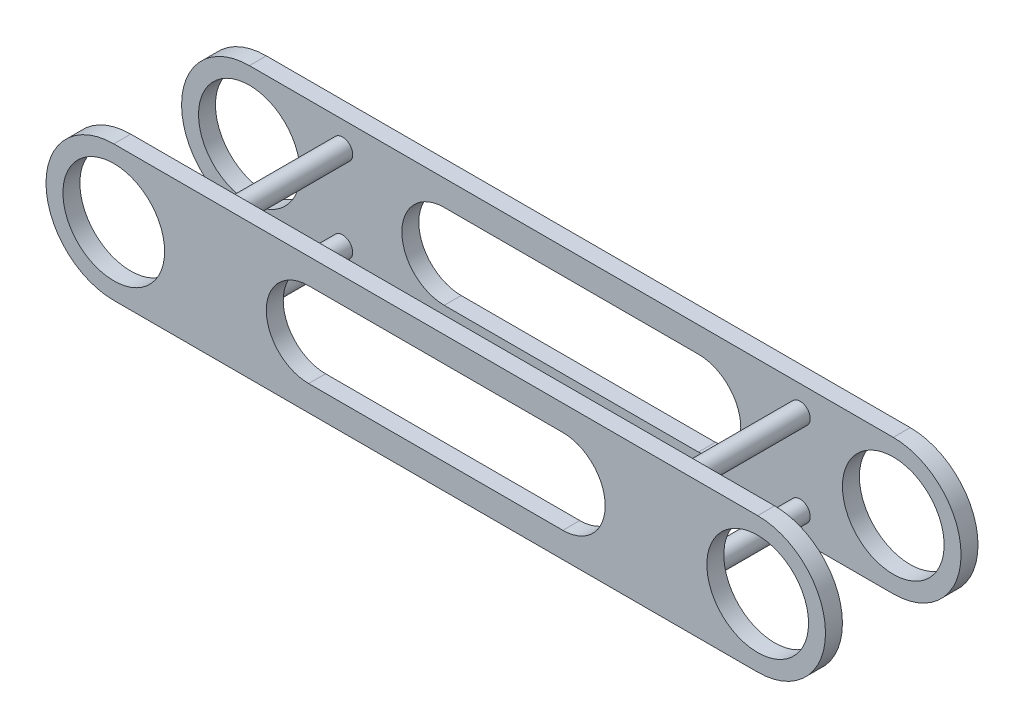
SolidWorks part; units mm, degrees
ref_plane "Front Plane" through (0, 0, 0) normal (0, 0, 1) x (1, 0, 0)
ref_plane "Top Plane" through (0, 0, 0) normal (0, 1, 0) x (1, 0, 0)
ref_plane "Right Plane" through (0, 0, 0) normal (1, 0, 0) x (0, 0, -1)
sketch "Sketch2" plane through (0, 0, 0) normal (0, 0, 1) x (1, 0, 0)
  circle A0 centre (0, 0) radius 30
  dimension "D1" = 60
extrude "Boss-Extrude1" add sketch "Sketch2" along normal mid plane 105
ref_plane "Plane1" through (0, 0, 45) normal (0, 0, 1) x (1, 0, 0)
sketch "Sketch3" plane through (0, 0, 45) normal (0, 0, 1) x (1, 0, 0)
  line L0 (0, -40) -> (0, 40) construction
  line L1 (0, 40) -> (380, 40)
  line L2 (0, 0) -> (380, 0) construction
  line L3 (380, -40) -> (380, 40) construction
  line L4 (0, -40) -> (380, -40)
  arc A0 (0, 40) -> (0, -40) centre (0, 0) ccw
  arc A1 (380, -40) -> (380, 40) centre (380, 0) ccw
  point P6 (0, 0)
  point P7 (0, 0)
  point P12 (380, 0)
  dimension "D1" = 40
  dimension "D2" = 380
extrude "Boss-Extrude2" add sketch "Sketch3" against normal blind 10
sketch "Sketch4" plane through (0, 0, 45) normal (0, 0, 1) x (1, 0, 0)
  line L0 (190, 40) -> (190, -40) construction
  line L1 (380, 40) -> (0, 40) construction
  line L2 (0, -40) -> (380, -40) construction
  line L3 (420, 0) -> (-40, 0) construction
  line L4 (265, 0) -> (115, 0) construction
  line L5 (265, -25) -> (115, -25)
  line L6 (265, 25) -> (115, 25)
  arc A0 (0, 40) -> (0, -40) centre (0, 0) ccw construction
  arc A1 (265, -25) -> (265, 25) centre (265, 0) ccw
  arc A2 (115, 25) -> (115, -25) centre (115, 0) ccw
  point P12 (190, 0)
  point P14 (190, 0)
  dimension "D2" = 25
  dimension "D1" = 150
extrude "Cut-Extrude1" cut sketch "Sketch4" against normal through all
sketch "Sketch5" plane through (0, 0, 0) normal (0, 0, 1) x (1, 0, 0)
  circle A0 centre (380, 0) radius 30
  dimension "D1" = 60
extrude "Boss-Extrude3" add sketch "Sketch5" along normal mid plane 105
mirror "Mirror1" about plane through (0, 0, 0) normal (0, 0, 1) of "Cut-Extrude1", "Boss-Extrude2"
sketch "Sketch7" plane through (0, 0, 45) normal (0, 0, 1) x (1, 0, 0)
  line L0 (0, 0) -> (380, 0) construction
  line L2 (325, -25) -> (55, -25) construction
  line L3 (325, -25) -> (325, 25) construction
  line L4 (325, 25) -> (55, 25) construction
  line L5 (55, -25) -> (55, 25) construction
  line L6 (325, -25) -> (55, 25) construction
  line L7 (325, 25) -> (55, -25) construction
  circle A0 centre (55, 25) radius 6
  circle A1 centre (325, 25) radius 6
  circle A2 centre (325, -25) radius 6
  circle A3 centre (55, -25) radius 6
  point P4 (190, 0)
  dimension "D3" = 12
  dimension "D1" = 270
  dimension "D2" = 50
extrude "Boss-Extrude4" add sketch "Sketch7" against normal up to surface (80 mm away) up to face at (190, 0, -35)
sketch "Sketch8" plane through (0, 0, 52.5) normal (0, 0, 1) x (1, 0, 0)
  circle A1 centre (0, 0) radius 30
  circle A2 centre (0, 0) radius 30
  circle A3 centre (380, 0) radius 30
  circle A4 centre (380, 0) radius 30
  dimension "D1" = 0
  dimension "D2" = 0
extrude "Cut-Extrude2" cut sketch "Sketch8" against normal through all
